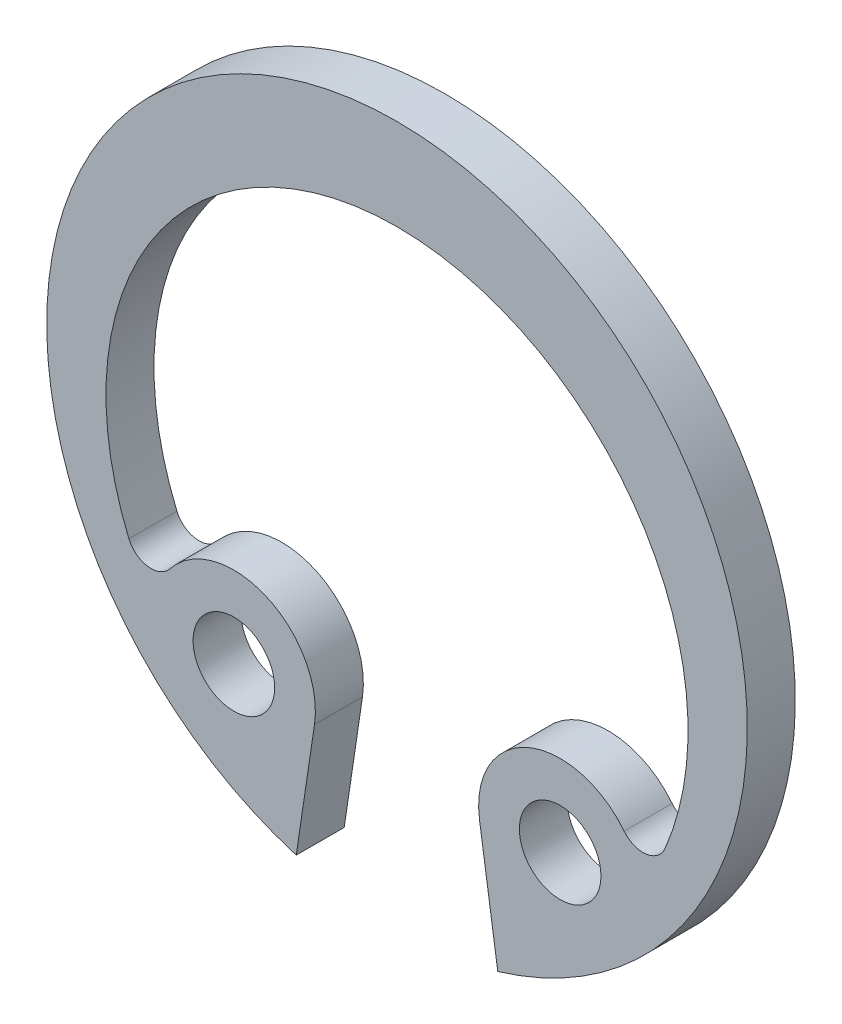
SolidWorks part; units mm, degrees
ref_plane "Front Plane" through (0, 0, 0) normal (0, 0, 1) x (1, 0, 0)
ref_plane "Top Plane" through (0, 0, 0) normal (0, 1, 0) x (1, 0, 0)
ref_plane "Right Plane" through (0, 0, 0) normal (1, 0, 0) x (0, 0, -1)
sketch "Sketch1" plane through (0, 0, 0) normal (0, 0, 1) x (1, 0, 0)
  line L0 (0, 0) -> (0, 7.3) construction
  line L1 (-1.7195, -4.4453) -> (-2.1, -6.9914)
  line L2 (1.7195, -4.4453) -> (2.1, -6.9914)
  line L3 (2.33, -2.8742) -> (4.597, -5.6708) construction
  arc A0 (2.1, -6.9914) -> (-2.1, -6.9914) centre (0, 0) ccw
  arc A1 (-5.5866, -3.026) -> (-4.7336, -3.1412) centre (-5.126, -2.8314) ccw
  circle A2 centre (-3.4, -4.1942) radius 0.85
  circle A3 centre (3.4, -4.1942) radius 0.85
  circle A4 centre (0, 0) radius 3.5 construction
  arc A6 (-1.7195, -4.4453) -> (-4.7336, -3.1412) centre (-3.4, -4.1942) ccw
  arc A7 (4.7336, -3.1412) -> (1.7195, -4.4453) centre (3.4, -4.1942) ccw
  arc A8 (5.5866, -3.026) -> (-5.5866, -3.026) centre (0, -0.665) ccw
  arc A9 (5.5866, -3.026) -> (4.7336, -3.1412) centre (5.126, -2.8314) cw
  point P13 (0, 5.4)
  dimension "RIC_D2_s" = 14.6
  dimension "RIC_D0_s" = 1.7
  dimension "D1" = 0.5
  dimension "RIC_D5_s" = 7
  dimension "RIC_MSM_2" = 6.8
  dimension "D2" = 17
  dimension "RIC_MSM_1" = 4.2
  dimension "RIC_B_s" = 1.9
  dimension "RIC_A_s" = 3.6
extrude "Boss-Extrude1" add sketch "Sketch1" along normal blind 1
equation "\"RIC_D4_s@Sketch1\"=\"RIC_D2_s@Sketch1\"-1.3*\"RIC_B_s@Sketch1\""
